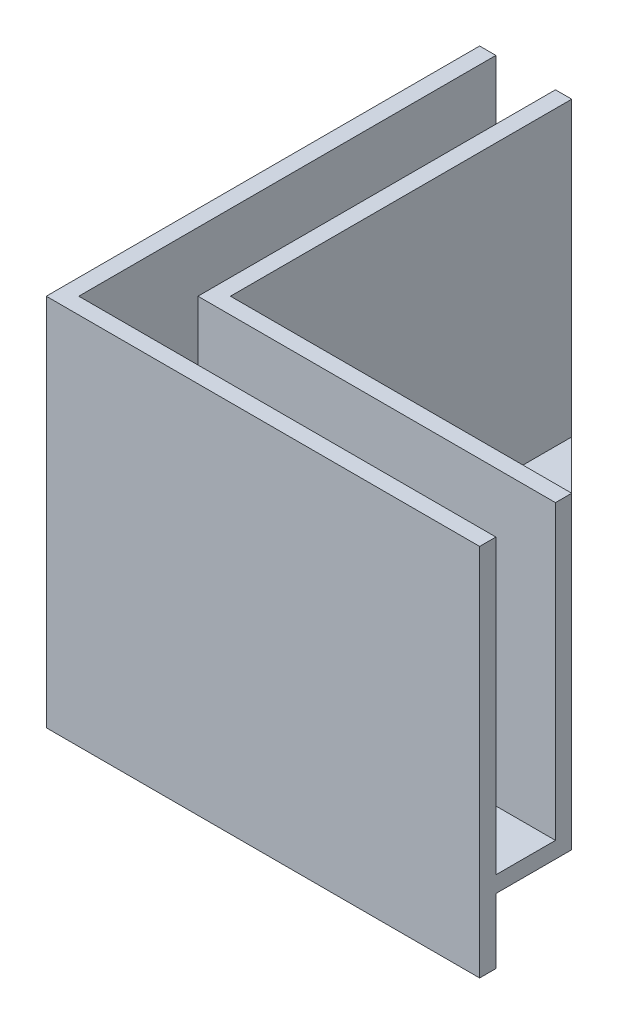
SolidWorks part; units mm, degrees
ref_plane "Front (XY)" through (0, 0, 0) normal (0, 0, 1) x (1, 0, 0)
ref_plane "Top (XZ)" through (0, 0, 0) normal (0, 1, 0) x (1, 0, 0)
ref_plane "Right (YZ)" through (0, 0, 0) normal (1, 0, 0) x (0, 0, -1)
sketch "Sketch1" plane through (0, 0, 0) normal (0, 1, 0) x (1, 0, 0)
  line L0 (0, 0) -> (0, 20)
  line L1 (0, 0) -> (20, 0)
  line L2 (0, 20) -> (4.25, 20)
  line L3 (20, 0) -> (20, 4.25)
  line L4 (4.25, 20) -> (4.25, 4.25)
  line L5 (20, 4.25) -> (4.25, 4.25)
  dimension "D1" = 20
  dimension "D2" = 20
  dimension "D3" = 4.25
  dimension "D4" = 4.25
extrude "Boss-Extrude1" add sketch "Sketch1" along normal blind 0.75
sketch "Sketch2" plane through (0, 0.75, 0) normal (0, 1, 0) x (1, 0, 0)
  line L0 (20, 3.5) -> (20, 4.25)
  line L1 (0.75, 20) -> (0, 20)
  line L6 (0, 0) -> (20, 0)
  line L7 (20, 0) -> (20, 4.25)
  line L8 (20, 4.25) -> (4.25, 4.25)
  line L9 (4.25, 4.25) -> (4.25, 20)
  line L10 (4.25, 20) -> (0, 20)
  line L11 (0, 20) -> (0, 0)
  line L12 (0.75, 0.75) -> (19.25, 0.75)
  line L13 (19.25, 0.75) -> (19.25, 3.5)
  line L14 (19.25, 3.5) -> (3.5, 3.5)
  line L15 (3.5, 3.5) -> (3.5, 19.25)
  line L16 (3.5, 19.25) -> (0.75, 19.25)
  line L17 (0.75, 19.25) -> (0.75, 0.75)
  line L18 (0.75, 0.75) -> (20, 0.75)
  line L20 (20, 3.5) -> (3.5, 3.5)
  line L21 (3.5, 3.5) -> (3.5, 20)
  line L23 (0.75, 20) -> (0.75, 0.75)
  line L24 (0, 0) -> (20, 0)
  line L25 (20, 0) -> (20, 0.75)
  line L26 (20, 4.25) -> (4.25, 4.25)
  line L27 (4.25, 4.25) -> (4.25, 20)
  line L28 (4.25, 20) -> (3.5, 20)
  line L29 (0, 20) -> (0, 0)
  dimension "D1" = 0.75
  dimension "D2" = 0
extrude "Boss-Extrude2" add sketch "Sketch2" along normal blind 13.5
sketch "Sketch4" plane through (0, 0, 0) normal (0, -1, 0) x (1, 0, 0)
  line L6 (20, 0) -> (0, 0)
  line L7 (0, 0) -> (0, -20)
  line L8 (0, -20) -> (4.25, -20)
  line L9 (4.25, -20) -> (4.25, -4.25)
  line L10 (4.25, -4.25) -> (20, -4.25)
  line L11 (20, -4.25) -> (20, 0)
  line L12 (20, 0) -> (0, 0)
  line L13 (0, 0) -> (0, -20)
  line L14 (0, -20) -> (20, -20)
  line L17 (20, -20) -> (20, 0)
  dimension "D1" = 0
extrude "Boss-Extrude3" add sketch "Sketch4" against normal blind 0.75
sketch "Sketch7" plane through (0, 0, 0) normal (0, -1, 0) x (1, 0, 0)
  line L6 (0, 0) -> (0, -20)
  line L7 (20, 0) -> (0, 0)
  line L8 (20, -0.75) -> (20, 0)
  line L9 (0.75, -0.75) -> (20, -0.75)
  line L10 (0.75, -20) -> (0.75, -0.75)
  line L11 (0, -20) -> (0.75, -20)
  line L12 (0, 0) -> (0, -20)
  line L13 (20, 0) -> (0, 0)
  line L14 (20, -0.75) -> (20, 0)
  line L15 (0.75, -0.75) -> (20, -0.75)
  line L16 (0.75, -20) -> (0.75, -0.75)
  line L17 (0, -20) -> (0.75, -20)
  dimension "D1" = 0
extrude "Boss-Extrude7" add sketch "Sketch7" along normal blind 3
sketch "Sketch8" plane through (0, 0.75, 0) normal (0, 1, 0) x (1, 0, 0)
  line L5 (20, 4.25) -> (20, 20)
  line L6 (20, 20) -> (4.25, 20)
  line L8 (20, 4.25) -> (4.25, 20)
extrude "Cut-Extrude1" cut sketch "Sketch8" against normal through all
